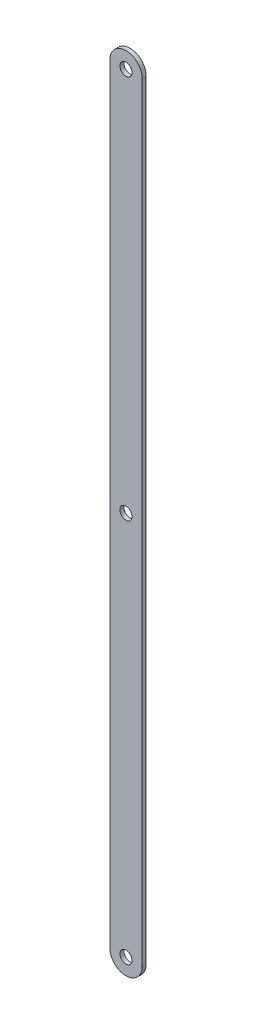
SolidWorks part; units mm, degrees
ref_plane "Front Plane" through (0, 0, 0) normal (0, 0, 1) x (1, 0, 0)
ref_plane "Top Plane" through (0, 0, 0) normal (0, 1, 0) x (1, 0, 0)
ref_plane "Right Plane" through (0, 0, 0) normal (1, 0, 0) x (0, 0, -1)
sketch "Sketch1" plane through (0, 0, 0) normal (0, 0, 1) x (1, 0, 0)
  line L0 (0, 475) -> (0, -475) construction
  line L1 (20, 475) -> (20, -475)
  line L2 (-20, 475) -> (-20, -475)
  arc A0 (20, 475) -> (-20, 475) centre (0, 475) ccw
  arc A1 (-20, -475) -> (20, -475) centre (0, -475) ccw
  circle A2 centre (0, 475) radius 7.5
  circle A3 centre (0, 0) radius 7.5
  circle A4 centre (0, -475) radius 7.5
  point P2 (0, 0)
  dimension "D2" = 20
  dimension "D3" = 15
  dimension "D4" = 15
  dimension "D5" = 15
  dimension "D1" = 950
extrude "Boss-Extrude1" add sketch "Sketch1" along normal blind 5
